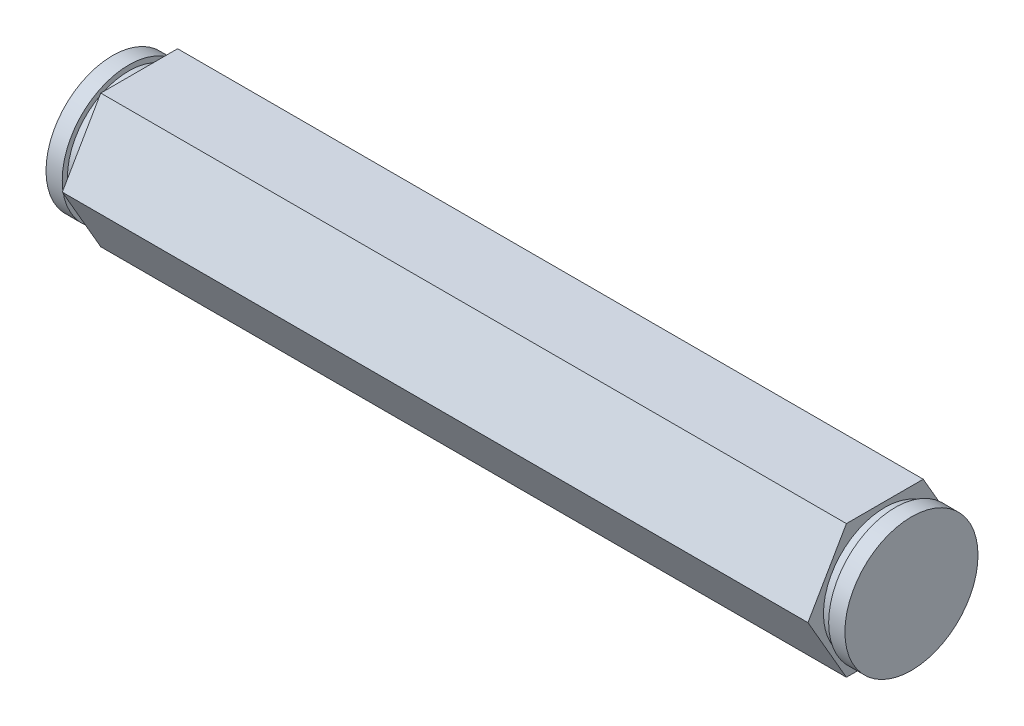
SolidWorks part; units mm, degrees
material "7075-T6 (SN)"
ref_plane "Front Plane" through (0, 0, 0) normal (0, 0, 1) x (1, 0, 0)
ref_plane "Top Plane" through (0, 0, 0) normal (0, 1, 0) x (1, 0, 0)
ref_plane "Right Plane" through (0, 0, 0) normal (1, 0, 0) x (0, 0, -1)
sketch "Sketch1" plane through (0, 0, 0) normal (1, 0, 0) x (0, 0, -1)
  line L1 (7.3323, 0) -> (3.6662, 6.35)
  line L2 (3.6662, 6.35) -> (-3.6662, 6.35)
  line L3 (-3.6662, 6.35) -> (-7.3323, 0)
  line L4 (-7.3323, 0) -> (-3.6662, -6.35)
  line L5 (-3.6662, -6.35) -> (3.6662, -6.35)
  line L6 (3.6662, -6.35) -> (7.3323, 0)
  circle A0 centre (0, 0) radius 6.35 construction
  dimension "D1" = 12.7
extrude "Boss-Extrude1" add sketch "Sketch1" along normal mid plane 76.2218
sketch "Sketch2" plane through (0, 0, 0) normal (0, 1, 0) x (1, 0, 0)
  line L0 (35.5709, -5.8547) -> (36.5615, -5.8547)
  line L1 (36.5615, -5.8547) -> (36.5615, -6.35)
  line L2 (36.5615, -6.35) -> (38.1109, -6.35)
  line L3 (38.1109, -6.35) -> (38.1109, -8.89)
  line L4 (38.1109, -8.89) -> (35.5709, -8.89)
  line L5 (35.5709, -8.89) -> (35.5709, -5.8547)
  line L6 (0, 0) -> (49.5443, 0) construction
  dimension "D1" = 2.54
  dimension "D2" = 6.35
  dimension "D3" = 5.8547
  dimension "D4" = 2.54
  dimension "D5" = 0.9906
revolve "Cut-Revolve1" cut sketch "Sketch2" angle 360 about L6
mirror "Mirror1" about plane through (0, 0, 0) normal (1, 0, 0) of "Cut-Revolve1"
